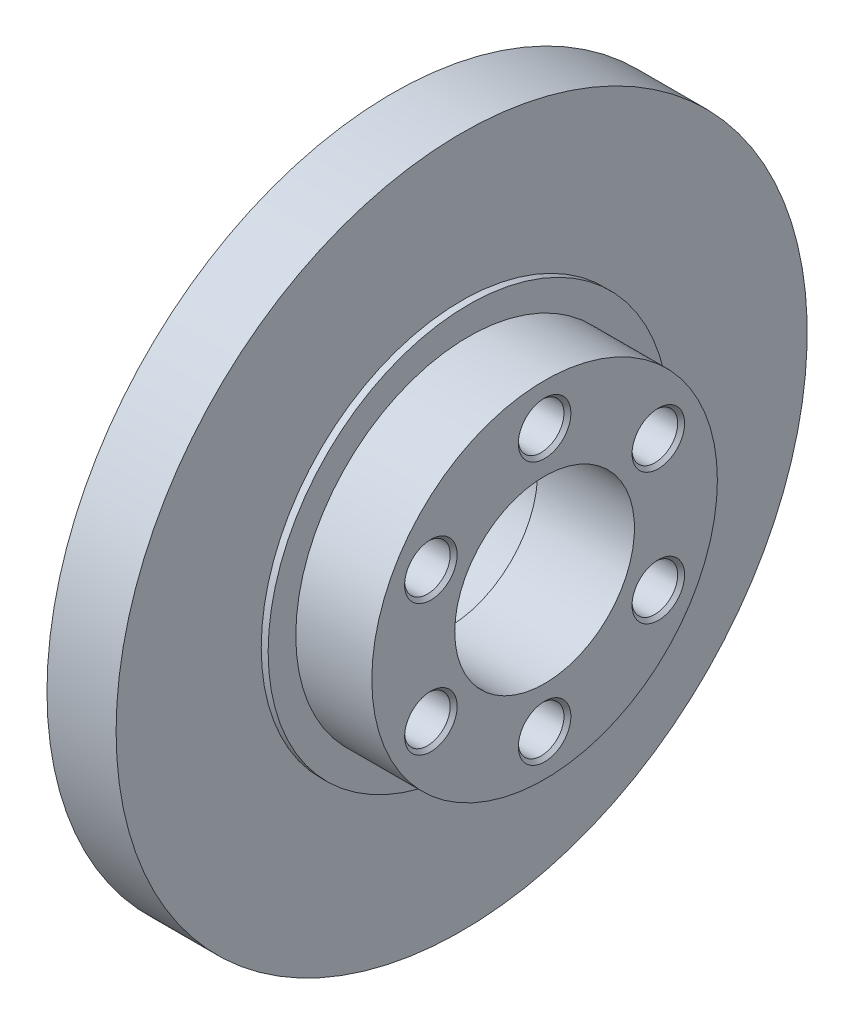
SolidWorks part; units mm, degrees
ref_plane "Front Plane" through (0, 0, 0) normal (0, 0, 1) x (1, 0, 0)
ref_plane "Top Plane" through (0, 0, 0) normal (0, 1, 0) x (1, 0, 0)
ref_plane "Right Plane" through (0, 0, 0) normal (1, 0, 0) x (0, 0, -1)
sketch "Sketch2" plane through (0, 0, 0) normal (0, 0, 1) x (1, 0, 0)
  line L0 (0, 50) -> (10, 50)
  line L1 (10, 50) -> (10, 29)
  line L2 (10, 29) -> (11, 29)
  line L3 (11, 29) -> (11, 25)
  line L4 (11, 25) -> (22, 25)
  line L5 (22, 25) -> (22, 13)
  line L6 (22, 13) -> (8, 13)
  line L9 (8, 13) -> (8, 14)
  line L10 (8, 14) -> (0, 14)
  line L11 (0, 14) -> (0, 50)
  line L12 (0, 0) -> (22, 0) construction
  dimension "D1" = 14
  dimension "D2" = 50
  dimension "D5" = 8
  dimension "14mm" = 14
  dimension "D8" = 1
  dimension "D9" = 10
  dimension "D10" = 4
  dimension "D3" = 12
  dimension "D4" = 13
revolve "Revolve1" add sketch "Sketch2" angle 360 about L12
sketch "Sketch3" plane through (0, 0, 0) normal (1, 0, 0) x (0, 0, -1)
  circle A0 centre (0, 0) radius 40 construction
  circle A1 centre (0, 40) radius 2.5
  circle A2 centre (28.2843, 28.2843) radius 2.5
  circle A3 centre (0, 0) radius 40 construction
  circle A4 centre (40, 0) radius 2.5
  circle A5 centre (0, 0) radius 40 construction
  circle A6 centre (28.2843, -28.2843) radius 2.5
  circle A7 centre (0, 0) radius 40 construction
  circle A8 centre (0, -40) radius 2.5
  circle A9 centre (0, 0) radius 40 construction
  circle A10 centre (-28.2843, -28.2843) radius 2.5
  circle A11 centre (0, 0) radius 40 construction
  circle A12 centre (-40, 0) radius 2.5
  circle A13 centre (0, 0) radius 40 construction
  circle A14 centre (-28.2843, 28.2843) radius 2.5
  circle A15 centre (0, 0) radius 40 construction
  point P29 (0, 0)
  dimension "D1" = 80
  dimension "D3" = 8
extrude "Cut-Extrude1" cut sketch "Sketch3" along normal blind 4
sketch "Sketch4" plane through (22, 0, 0) normal (1, 0, 0) x (0, 0, -1)
  circle A0 centre (0, 0) radius 19 construction
  circle A1 centre (0, 19) radius 3.3
  circle A2 centre (16.4545, 9.5) radius 3.3
  circle A3 centre (16.4545, -9.5) radius 3.3
  circle A4 centre (0, -19) radius 3.3
  circle A5 centre (-16.4545, -9.5) radius 3.3
  circle A6 centre (-16.4545, 9.5) radius 3.3
  point P17 (0, 0)
  dimension "D1" = 38
  dimension "D2" = 6.6
  dimension "D3" = 6
extrude "Cut-Extrude2" cut sketch "Sketch4" against normal blind 10
chamfer "Chamfer1" distance 0.5 angle 45 6 edges at (22, 9.5, 13.1545) (22, -9.5, 13.1545) (22, -19, -3.3) (22, -9.5, -19.7545) (22, 9.5, -19.7545) (22, 19, -3.3)
equation "\"R_ROLL\"= 5mm"
equation "\"D_SUN\"= 120mm"
equation "\"NUM_ROLL\"= 31"
equation "\"RHO\"= 1mm"
equation "\"D_SHAFT\"= 28mm"
equation "\"D_OUTPUT\"= 80mm"
equation "\"NUM_OUT\"= 8"
equation "\"R_OUT_ROLL\"= 5mm"
equation "\"D1@Sketch2\"=\"D_SHAFT\"/2"
equation "\"D2@Sketch2\"=\"D_OUTPUT\"/2+10"
equation "\"D1@Sketch3\"=\"D_OUTPUT\""
